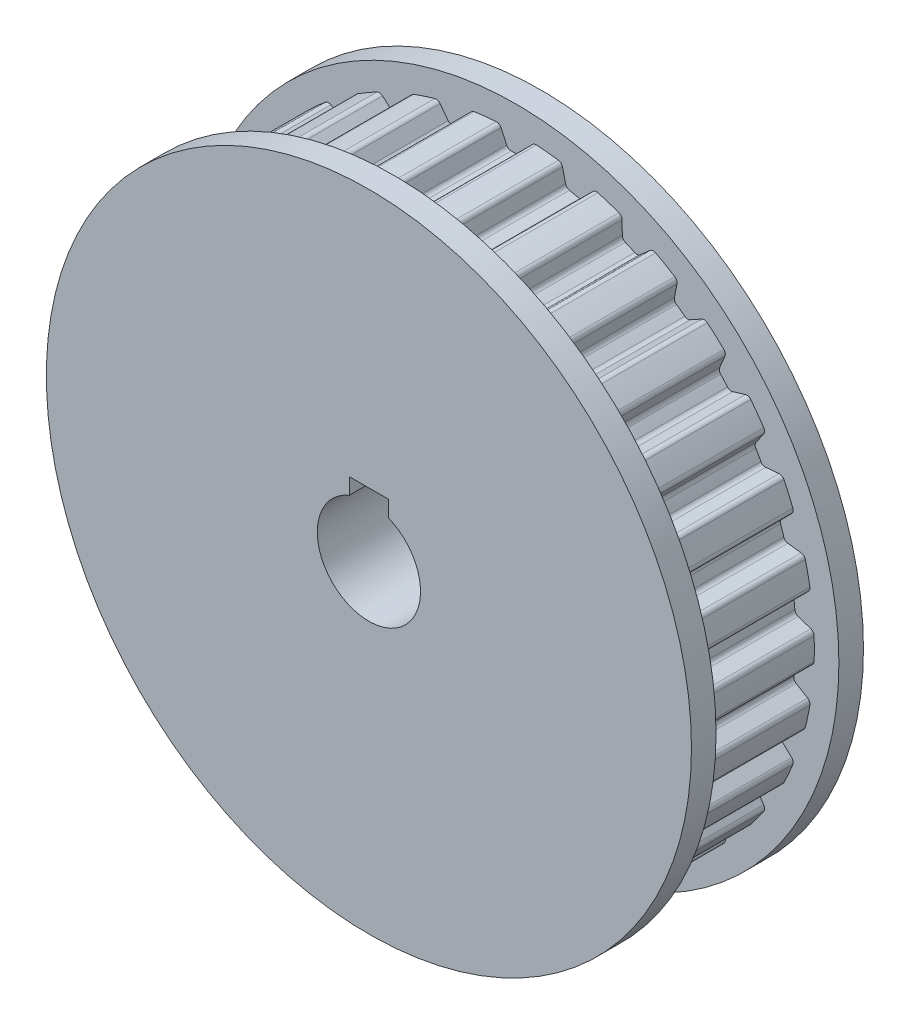
SolidWorks part; units mm, degrees
ref_plane "Front Plane" through (0, 0, 0) normal (0, 0, 1) x (1, 0, 0)
ref_plane "Top Plane" through (0, 0, 0) normal (0, 1, 0) x (1, 0, 0)
ref_plane "Right Plane" through (0, 0, 0) normal (1, 0, 0) x (0, 0, -1)
sketch "Sketch1" plane through (0, 0, 0) normal (0, 1, 0) x (1, 0, 0)
  line L0 (0, 0) -> (0, 21.1203) construction
  line L3 (0, 14) -> (-26.2552, 14)
  line L4 (-26.2552, 14) -> (-26.2552, 12)
  line L5 (-26.2552, 12) -> (-24.2552, 12)
  line L6 (-24.2552, 12) -> (-24.2552, 2)
  line L7 (-24.2552, 2) -> (-26.2552, 2)
  line L8 (-26.2552, 2) -> (-26.2552, 0)
  line L9 (-26.2552, 0) -> (0, 0)
  line L10 (0, 0) -> (0, 14)
  line L11 (-26.2552, 12) -> (-26.2552, 2) construction
  dimension "D1" = 24.2552
  dimension "D2" = 2
  dimension "D3" = 10
  dimension "D4" = 2
  dimension "D5" = 2
revolve "Revolve1" add sketch "Sketch1" angle 360 about L10
ref_plane "Plane1" through (0, 0, -7) normal (0, 0, 1) x (1, 0, 0)
sketch "Sketch6" plane through (0, 0, -7) normal (0, 0, 1) x (1, 0, 0)
  line L0 (0, 0) -> (0, 10.2344) construction
  line L1 (-0.7897, 22.9822) -> (-1.2502, 23.9697)
  line L2 (0.7897, 22.9822) -> (1.2502, 23.9697)
  arc A0 (0.4198, 22.7513) -> (-0.4198, 22.7513) centre (0, 0) ccw
  arc A1 (-0.4198, 22.7513) -> (-0.7897, 22.9822) centre (-0.4272, 23.1513) cw
  arc A2 (0.4198, 22.7513) -> (0.7897, 22.9822) centre (0.4272, 23.1513) ccw
  arc A3 (-1.2502, 23.9697) -> (-1.6397, 24.1997) centre (-1.6127, 23.8006) ccw
  arc A4 (1.2502, 23.9697) -> (1.6397, 24.1997) centre (1.6127, 23.8006) cw
  arc A5 (-1.6397, 24.1997) -> (1.6397, 24.1997) centre (0, 0) cw
  circle A6 centre (0, 0) radius 24.2552 construction
  arc A7 (0.7848, 22.9718) -> (-0.7848, 22.9718) centre (0, 0) ccw construction
  point P15 (0, 22.7552)
  point P20 (0, 24.2552)
  dimension "D2" = 0.4
  dimension "D3" = 0.4
  dimension "D4" = 1.5
  dimension "D5" = 1.27
  dimension "D6" = 1.57
  dimension "D1" = 50
extrude "Cut-Extrude4" cut sketch "Sketch6" against normal up to surface and the other way up to surface up to face at (24.2552, 0, -12) other way up to face at (26.2552, 0, -2)
pattern_circular "CirPattern1" count 30 over 360 about axis through (0, 0, 0) along (0, 0, 1) of "Cut-Extrude4"
sketch "Sketch2" plane through (0, 0, 0) normal (0, 0, 1) x (1, 0, 0)
  circle A0 centre (0, 0) radius 4.2
  circle A1 centre (0, 0) radius 26.2552 construction
  dimension "D1" = 8.4
extrude "Cut-Extrude1" cut sketch "Sketch2" against normal through all
sketch "Sketch7" plane through (0, 0, 0) normal (0, 0, 1) x (1, 0, 0)
  line L1 (-1.6, 5.2) -> (1.6, 5.2)
  line L2 (-1.6, 5.2) -> (-1.6, 0)
  line L3 (-1.6, 0) -> (1.6, 0)
  line L4 (1.6, 5.2) -> (1.6, 0)
  circle A2 centre (0, 0) radius 4.2 construction
  point P4 (0, 0)
  dimension "D1" = 3.2
  dimension "D2" = 1
extrude "Cut-Extrude5" cut sketch "Sketch7" against normal through all
sketch "Sketch3" plane through (0, 0, 0) normal (0, 1, 0) x (1, 0, 0)
  line L2 (-28.8807, 7) -> (28.8807, 7) construction
  circle A0 centre (0, 7) radius 1.25
  dimension "D2" = 2.5
extrude "Cut-Extrude2" cut sketch "Sketch3" against normal through all
sketch "Sketch4" plane through (0, 0, 0) normal (1, 0, 0) x (0, 0, -1)
  line L2 (7, 28.8807) -> (7, -28.8807) construction
  circle A0 centre (7, 0) radius 1.25
  dimension "D2" = 2.5
extrude "Cut-Extrude3" cut sketch "Sketch4" against normal through all
equation "\"teeth\"= 30"
equation "\"pitch\"= 0.2in"
equation "\"pitch diameter\"= \"teeth\" * \"pitch\" / pi"
equation "\"D1@Sketch1\"=\"pitch diameter\"/2"
equation "\"D1@CirPattern1\"=\"teeth\""
